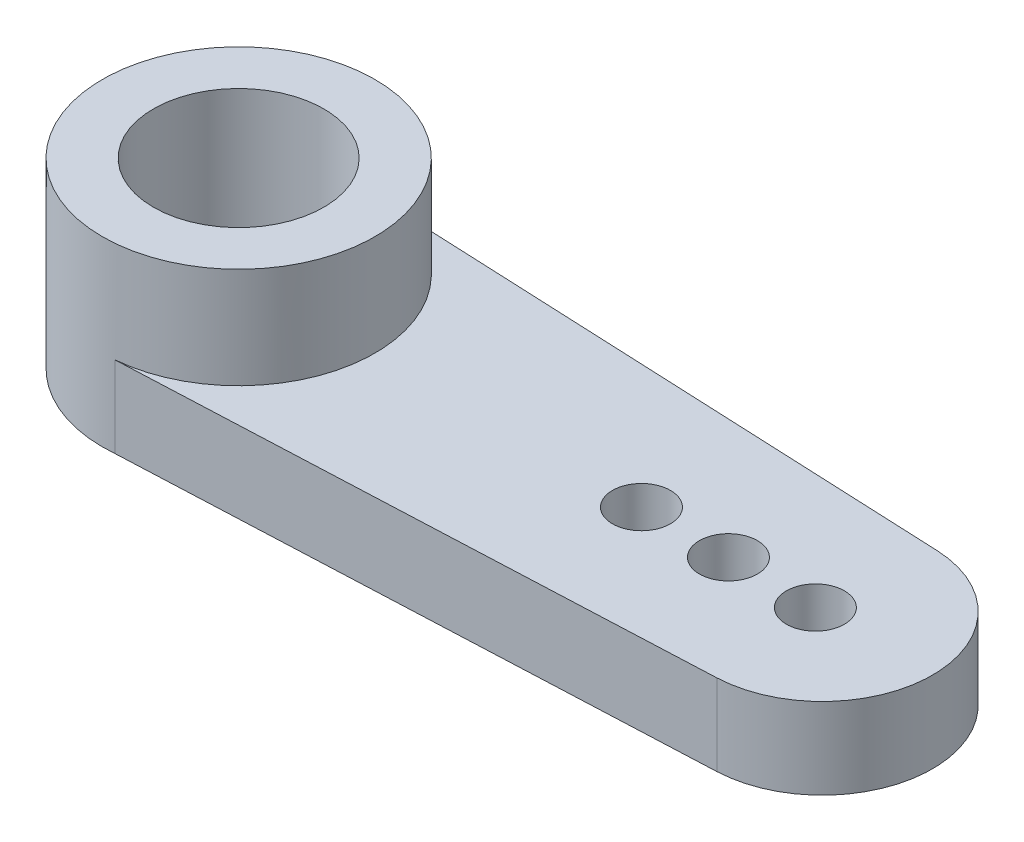
SolidWorks part; units mm, degrees
ref_plane "Front Plane" through (0, 0, 0) normal (0, 0, 1) x (1, 0, 0)
ref_plane "Top Plane" through (0, 0, 0) normal (0, 1, 0) x (1, 0, 0)
ref_plane "Right Plane" through (0, 0, 0) normal (1, 0, 0) x (0, 0, -1)
sketch "Sketch1" plane through (0, 0, 0) normal (0, 1, 0) x (1, 0, 0)
  circle A0 centre (0, 0) radius 2.9845
  circle A1 centre (0, 0) radius 1.8669
  dimension "D1" = 5.969
  dimension "D2" = 3.7338
extrude "Boss-Extrude1" add sketch "Sketch1" along normal blind 3.9878
sketch "Sketch2" plane through (0, 0, 0) normal (0, -1, 0) x (1, 0, 0)
  line L0 (0, 2.9845) -> (12.8905, 2.413)
  line L1 (0, -2.9845) -> (12.8905, -2.413)
  line L2 (-2.9845, 0) -> (-2.9845, 9.9842) construction
  circle A0 centre (0, 0) radius 2.9845 construction
  arc A1 (12.8905, 2.413) -> (12.8905, -2.413) centre (12.7835, 0) cw
  arc A2 (0, -2.9845) -> (0, 2.9845) centre (0, 0) ccw
  circle M1 centre (0, 0) radius 2.9845
  dimension "D2" = 4.826
  dimension "D1" = 15.875
extrude "Boss-Extrude2" add sketch "Sketch2" against normal blind 1.778 contours A1 L0 L1 M1
sketch "Sketch3" plane through (0, 0, 0) normal (0, -1, 0) x (1, 0, 0)
  line L0 (11.3635, 0) -> (11.3635, 1.9948) construction
  line L1 (11.9985, 0) -> (11.9985, 1.7434) construction
  line L2 (10.0935, 0) -> (10.0935, 1.6934) construction
  line L3 (9.4585, 0) -> (9.4585, 1.9948) construction
  circle A0 centre (8.8235, 0) radius 0.635
  circle A1 centre (10.7285, 0) radius 0.635
  circle A2 centre (12.6335, 0) radius 0.635
  arc A3 (12.8905, -2.413) -> (12.8905, 2.413) centre (12.7835, 0) ccw construction
  point P15 (15.1989, 0)
  dimension "D1" = 1.27
  dimension "D2" = 0.635
  dimension "D3" = 0.635
  dimension "D4" = 5.7404
extrude "Cut-Extrude1" cut sketch "Sketch3" against normal through all
